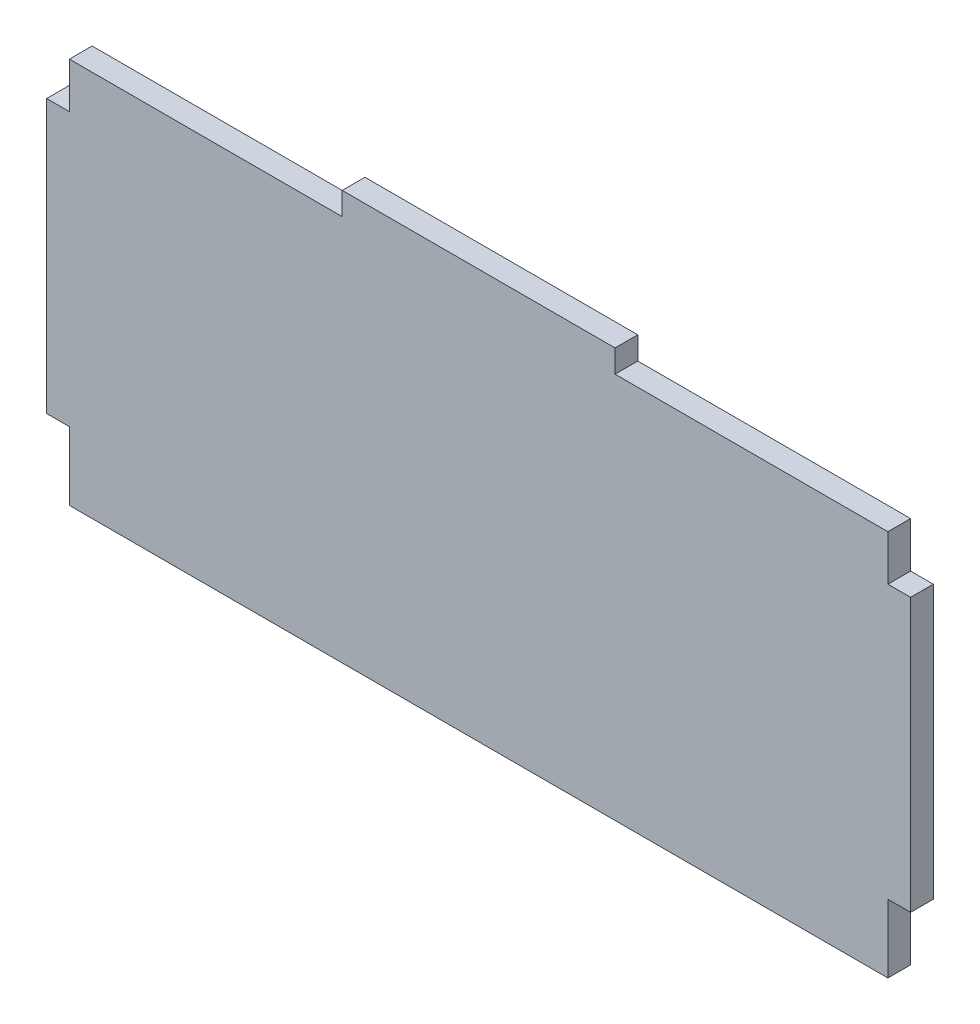
SolidWorks part; units mm, degrees
ref_plane "Front Plane" through (0, 0, 0) normal (0, 0, 1) x (1, 0, 0)
ref_plane "Top Plane" through (0, 0, 0) normal (0, 1, 0) x (1, 0, 0)
ref_plane "Right Plane" through (0, 0, 0) normal (1, 0, 0) x (0, 0, -1)
sketch "Sketch1" plane through (0, 0, 0) normal (0, 0, 1) x (1, 0, 0)
  line L0 (185.3837, 2.969) -> (185.3837, 43.298) construction
  line L1 (-49.5663, 19.0519) -> (179.0337, 19.0519)
  line L2 (-49.5663, 19.0519) -> (-49.5663, -88.8981)
  line L3 (-49.5663, -88.8981) -> (179.0337, -88.8981)
  line L4 (179.0337, 19.0519) -> (179.0337, -88.8981)
  line L5 (-55.9163, 6.3519) -> (-49.5663, 6.3519)
  line L6 (-55.9163, 6.3519) -> (-55.9163, -69.8481)
  line L7 (-55.9163, -69.8481) -> (-49.5663, -69.8481)
  line L8 (-49.5663, 6.3519) -> (-49.5663, -69.8481)
  line L9 (179.0337, 6.3519) -> (185.3837, 6.3519)
  line L10 (179.0337, 6.3519) -> (179.0337, -69.8481)
  line L11 (179.0337, -69.8481) -> (185.3837, -69.8481)
  line L12 (185.3837, 6.3519) -> (185.3837, -69.8481)
  line L13 (26.6337, 25.4019) -> (102.8337, 25.4019)
  line L14 (26.6337, 25.4019) -> (26.6337, 19.0519)
  line L15 (26.6337, 19.0519) -> (102.8337, 19.0519)
  line L16 (102.8337, 25.4019) -> (102.8337, 19.0519)
  dimension "D1" = 228.6
  dimension "D2" = 107.95
  dimension "D3" = 76.2
  dimension "D5" = 6.35
  dimension "D6" = 6.35
  dimension "D7" = 76.2
  dimension "D9" = 6.35
  dimension "D10" = 76.2
  dimension "D11" = 76.2
  dimension "D4" = 12.7
  dimension "D8" = 12.7
extrude "Boss-Extrude1" add sketch "Sketch1" along normal blind 6.35 contours L4 L1 L2 L3 | L16 L13 L14 L1 | L12 L9 L4 L11 | L6 L7 L2 L5
equation "\"width\"= 9in"
equation "\"Height\"= 18in"
equation "\"thick\"= 0.25"
equation "\"D1@Sketch1\"=\"width\""
equation "\"D2@Sketch1\"=(\"width\"/2)-\"thick\""
equation "\"D5@Sketch1\"=\"thick\""
equation "\"D6@Sketch1\"=\"thick\""
equation "\"D7@Sketch1\"=3"
equation "\"D9@Sketch1\"=\"thick\""
equation "\"D1@Boss-Extrude1\"=\"thick\""
equation "\"D4@Sketch1\"=0.75-\"thick\""
equation "\"D8@Sketch1\"=0.75-\"thick\""
